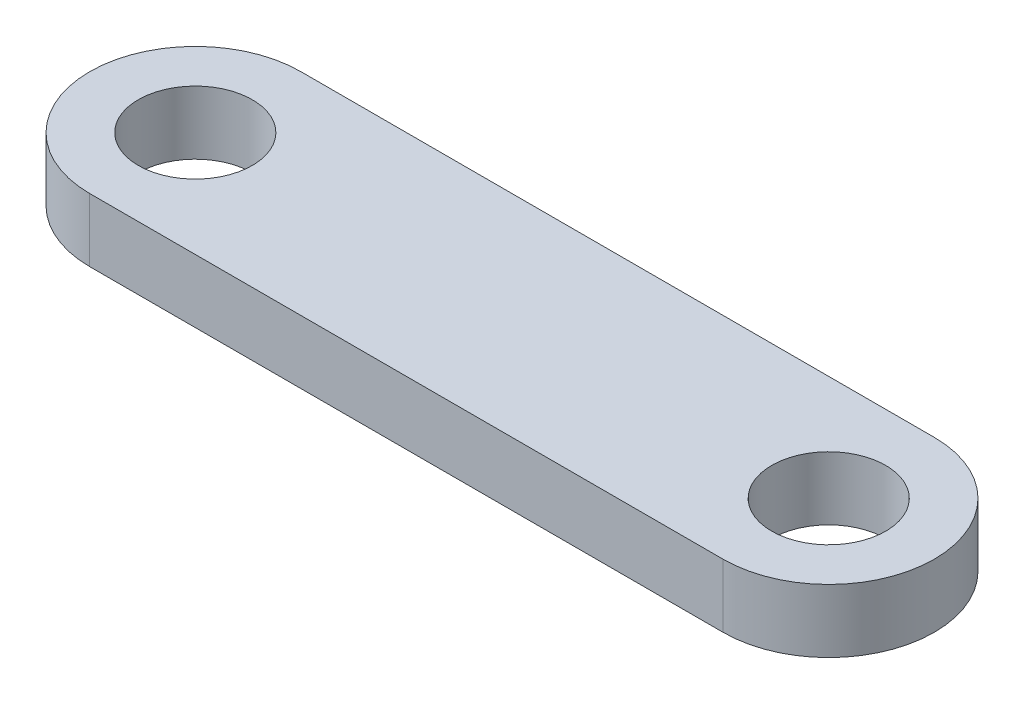
SolidWorks part; units mm, degrees
ref_plane "Front Plane" through (0, 0, 0) normal (0, 0, 1) x (1, 0, 0)
ref_plane "Top Plane" through (0, 0, 0) normal (0, 1, 0) x (1, 0, 0)
ref_plane "Right Plane" through (0, 0, 0) normal (1, 0, 0) x (0, 0, -1)
sketch "Sketch1" plane through (0, 0, 0) normal (0, 1, 0) x (1, 0, 0)
  line L0 (0, 0) -> (30, 0) construction
  line L1 (0, 5) -> (30, 5)
  line L2 (0, -5) -> (30, -5)
  arc A0 (0, 5) -> (0, -5) centre (0, 0) ccw
  arc A1 (30, -5) -> (30, 5) centre (30, 0) ccw
  circle A2 centre (0, 0) radius 2.7
  circle A3 centre (30, 0) radius 2.7
  point P3 (15, 0)
  dimension "D2" = 5
  dimension "D3" = 5.4
  dimension "D4" = 5.4
  dimension "D1" = 30
extrude "Boss-Extrude1" add sketch "Sketch1" along normal blind 3
